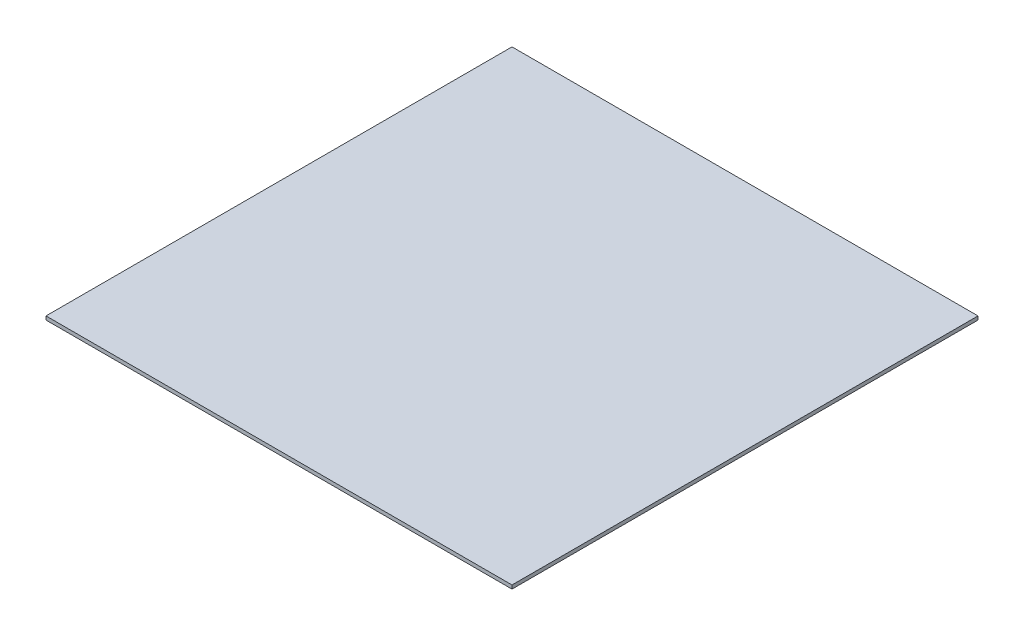
SolidWorks part; units mm, degrees
ref_plane "Front Plane" through (0, 0, 0) normal (0, 0, 1) x (1, 0, 0)
ref_plane "Top Plane" through (0, 0, 0) normal (0, 1, 0) x (1, 0, 0)
ref_plane "Right Plane" through (0, 0, 0) normal (1, 0, 0) x (0, 0, -1)
sketch "Sketch1" plane through (0, 0, 0) normal (0, 1, 0) x (1, 0, 0)
  line L1 (-83.9081, -48.561) -> (30.3919, -48.561)
  line L2 (-83.9081, -48.561) -> (-83.9081, 65.739)
  line L3 (-83.9081, 65.739) -> (30.3919, 65.739)
  line L4 (30.3919, -48.561) -> (30.3919, 65.739)
  dimension "D1" = 114.3
  dimension "D2" = 114.3
extrude "Boss-Extrude1" add sketch "Sketch1" along normal blind 0.889
